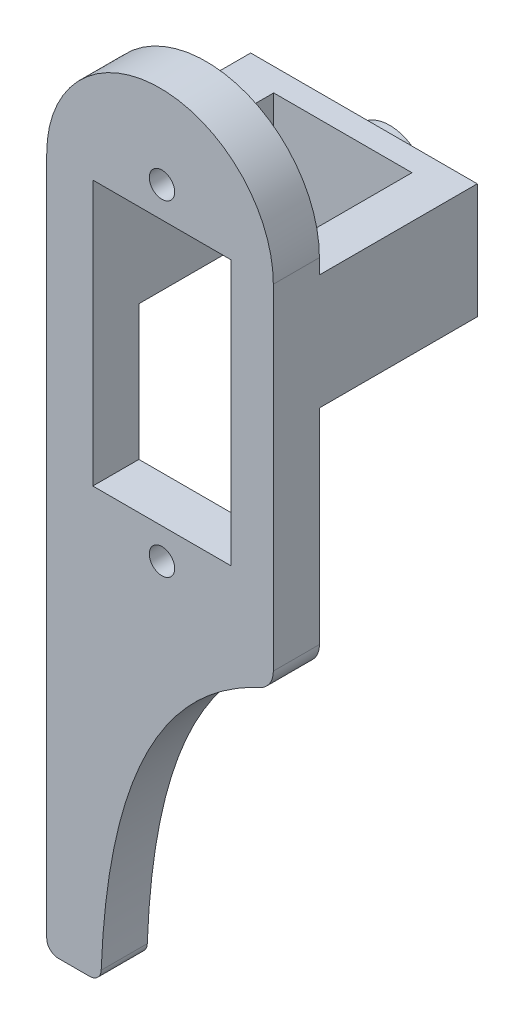
SolidWorks part; units mm, degrees
ref_plane "Front Plane" through (0, 0, 0) normal (0, 0, 1) x (1, 0, 0)
ref_plane "Top Plane" through (0, 0, 0) normal (0, 1, 0) x (1, 0, 0)
ref_plane "Right Plane" through (0, 0, 0) normal (1, 0, 0) x (0, 0, -1)
sketch "Sketch1" plane through (0, 0, 0) normal (0, 0, 1) x (1, 0, 0)
  line L0 (10.2196, 1.4347) -> (10.2196, -58.5653)
  line L4 (10.2196, -58.5653) -> (14.9213, -58.5653)
  line L5 (14.9213, -58.5653) -> (14.9213, -58.3072)
  line L6 (29.8859, -28.97) -> (29.8859, 1.4347)
  arc A1 (10.2196, 1.4347) -> (29.8859, 1.4347) centre (20.0527, 1.4347) cw
  spline S0 degree 2 poles (29.8859, -28.97) (15.6039, -34.5286) (14.9213, -58.3072) knots 0 0 0 1 1 1
  dimension "D2" = 9.8332
  dimension "D1" = 60
extrude "Boss-Extrude1" add sketch "Sketch1" along normal blind 4
sketch "Sketch2" plane through (0, 0, 4) normal (0, 0, 1) x (1, 0, 0)
  line L0 (10.2196, 1.4347) -> (14.2196, 1.4347) construction
  line L1 (14.2196, 1.4347) -> (26.2196, 1.4347)
  line L2 (14.2196, 1.4347) -> (14.2196, -21.5653)
  line L3 (14.2196, -21.5653) -> (26.2196, -21.5653)
  line L4 (26.2196, 1.4347) -> (26.2196, -21.5653)
  line L5 (10.2196, 1.4347) -> (10.2196, -58.5653) construction
  line L8 (20.2196, 4.0847) -> (20.2196, 1.4347) construction
  line L9 (20.2196, -21.5653) -> (20.2196, -24.2153) construction
  circle A0 centre (20.2196, 4.0847) radius 1.1
  circle A1 centre (20.2196, -24.2153) radius 1.1
  dimension "D4" = 2.2
  dimension "D1" = 23
  dimension "D2" = 12
  dimension "D3" = 4
  dimension "D5" = 2.65
  dimension "D6" = 2.65
extrude "Cut-Extrude1" cut sketch "Sketch2" against normal up to next
fillet "Fillet1" radius 2 1 edges at (29.8859, -28.97, 2)
fillet "Fillet2" radius 1 1 edges at (14.9213, -58.5653, 2)
fillet "Fillet3" radius 1 1 edges at (10.2196, -58.5653, 2)
sketch "Sketch3" plane through (0, 0, 0) normal (0, 0, -1) x (-1, 0, 0)
  line L0 (-29.8859, -27.6468) -> (-29.8859, 1.4347) construction
  line L1 (-29.8859, 0.1347) -> (-26.2196, 0.1347)
  line L2 (-29.8859, 0.1347) -> (-29.8859, -9.8653)
  line L3 (-29.8859, -9.8653) -> (-26.2196, -9.8653)
  line L4 (-26.2196, 0.1347) -> (-26.2196, -9.8653)
  line L5 (-26.2196, -21.5653) -> (-26.2196, 1.4347) construction
  line L6 (-14.2196, 1.4347) -> (-14.2196, -21.5653) construction
  line L7 (-14.2196, 0.1347) -> (-10.2196, 0.1347)
  line L8 (-14.2196, 0.1347) -> (-14.2196, -9.8653)
  line L9 (-14.2196, -9.8653) -> (-10.2196, -9.8653)
  line L10 (-10.2196, 0.1347) -> (-10.2196, -9.8653)
  line L11 (-10.2196, 1.4347) -> (-10.2196, -57.5653) construction
  line L12 (-26.2196, 1.4347) -> (-14.2196, 1.4347) construction
  dimension "D1" = 10
  dimension "D2" = 1.3
  dimension "D3" = 1.3
extrude "Boss-Extrude2" add sketch "Sketch3" along normal blind 11.7
sketch "Sketch4" plane through (0, 0, -11.7) normal (0, 0, -1) x (-1, 0, 0)
  line L1 (-29.8859, 0.1347) -> (-10.2196, 0.1347)
  line L2 (-29.8859, 0.1347) -> (-29.8859, -9.8653)
  line L3 (-29.8859, -9.8653) -> (-10.2196, -9.8653)
  line L4 (-10.2196, 0.1347) -> (-10.2196, -9.8653)
extrude "Boss-Extrude3" add sketch "Sketch4" along normal blind 2
sketch "Sketch5" plane through (0, 0, -13.7) normal (0, 0, -1) x (-1, 0, 0)
  line L0 (-29.8859, 0.1347) -> (-29.8859, -9.8653) construction
  line L2 (-10.2196, 0.1347) -> (-29.8859, 0.1347) construction
  circle A0 centre (-20.2859, -4.6653) radius 3.4
  dimension "D1" = 6.8
  dimension "D2" = 9.6
  dimension "D3" = 4.8
extrude "Boss-Extrude4" add sketch "Sketch5" along normal blind 2
